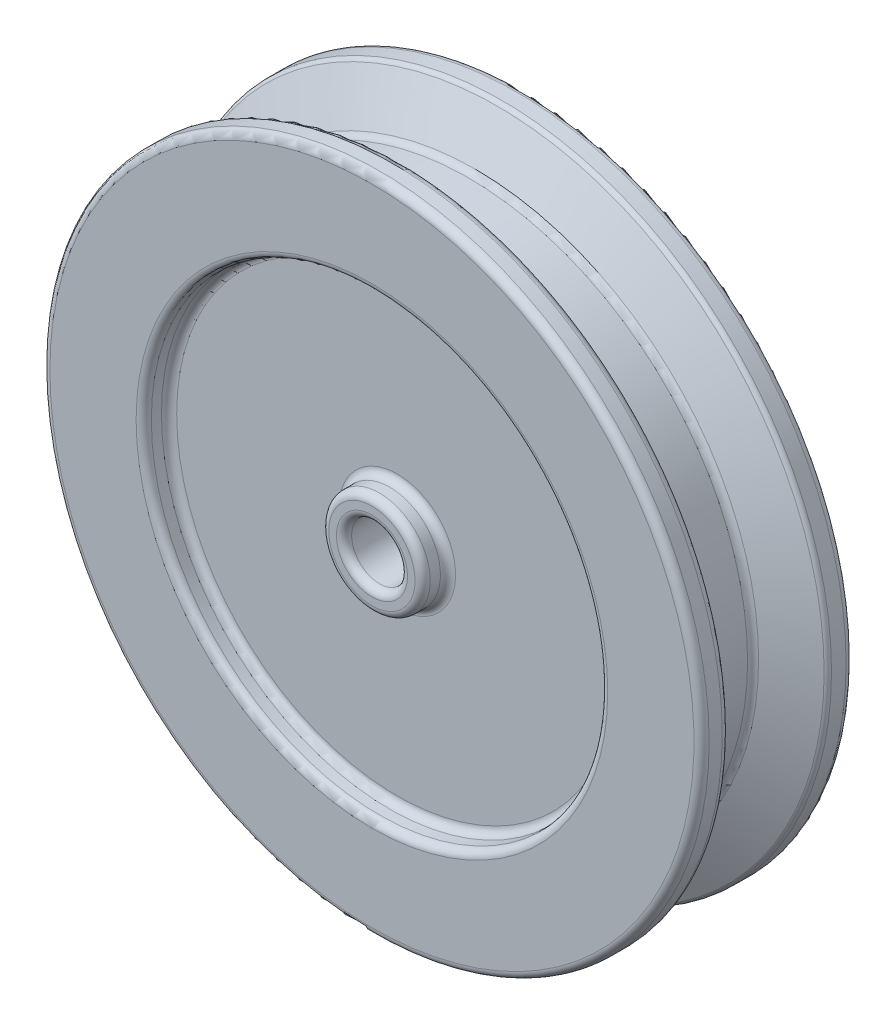
SolidWorks part; units mm, degrees
ref_plane "Front Plane" through (0, 0, 0) normal (0, 0, 1) x (1, 0, 0)
ref_plane "Top Plane" through (0, 0, 0) normal (0, 1, 0) x (1, 0, 0)
ref_plane "Right Plane" through (0, 0, 0) normal (1, 0, 0) x (0, 0, -1)
sketch "Sketch1" plane through (0, 0, 0) normal (1, 0, 0) x (0, 0, -1)
  line L0 (0, 0) -> (0, 9.3815) construction
  line L1 (0, 0) -> (11.8575, 0) construction
  line L2 (0, 2.794) -> (7.62, 2.794)
  line L3 (7.62, 2.794) -> (7.62, 5.08)
  line L4 (7.62, 5.08) -> (5.08, 5.08)
  line L5 (5.08, 5.08) -> (5.08, 22.86)
  line L6 (5.08, 22.86) -> (7.62, 22.86)
  line L7 (7.62, 22.86) -> (7.62, 33.02)
  line L8 (7.62, 33.02) -> (5.08, 33.02)
  line L9 (5.08, 33.02) -> (2.54, 27.94)
  line L10 (2.54, 27.94) -> (0, 27.94)
  line L11 (0, 27.94) -> (0, 2.794)
  line L12 (0, 9.3815) -> (0, 15.8327) construction
  line L13 (2.54, 35.6158) -> (2.54, 27.94) construction
  dimension "D1" = 2.794
  dimension "D2" = 5.08
  dimension "D3" = 22.86
  dimension "D4" = 33.02
  dimension "D5" = 7.62
  dimension "D6" = 7.62
  dimension "D7" = 2.54
  dimension "D8" = 2.54
  dimension "D9" = 5.08
  dimension "D10" = 2.54
revolve "Revolve1" add sketch "Sketch1" angle 360 about L1
mirror "Mirror1" about plane through (0, 27.94, 0) normal (0, 0, -1) of "Revolve1"
fillet "Fillet17" radius 0.762 15 edges at (27.94, 0, -2.54) (5.08, 0, -5.08) (2.794, 0, -7.62) (5.08, 0, -7.62) (22.86, 0, -5.08) (22.86, 0, -7.62) (33.02, 0, -7.62) (5.08, 0, 7.62) (2.794, 0, 7.62) (5.08, 0, 5.08) (22.86, 0, 5.08) (22.86, 0, 7.62) (33.02, 0, 7.62) (33.02, 0, 5.08) (27.94, 0, 2.54)
fillet "Fillet22" radius 0.508 1 edges at (33.02, 0, -5.08)
